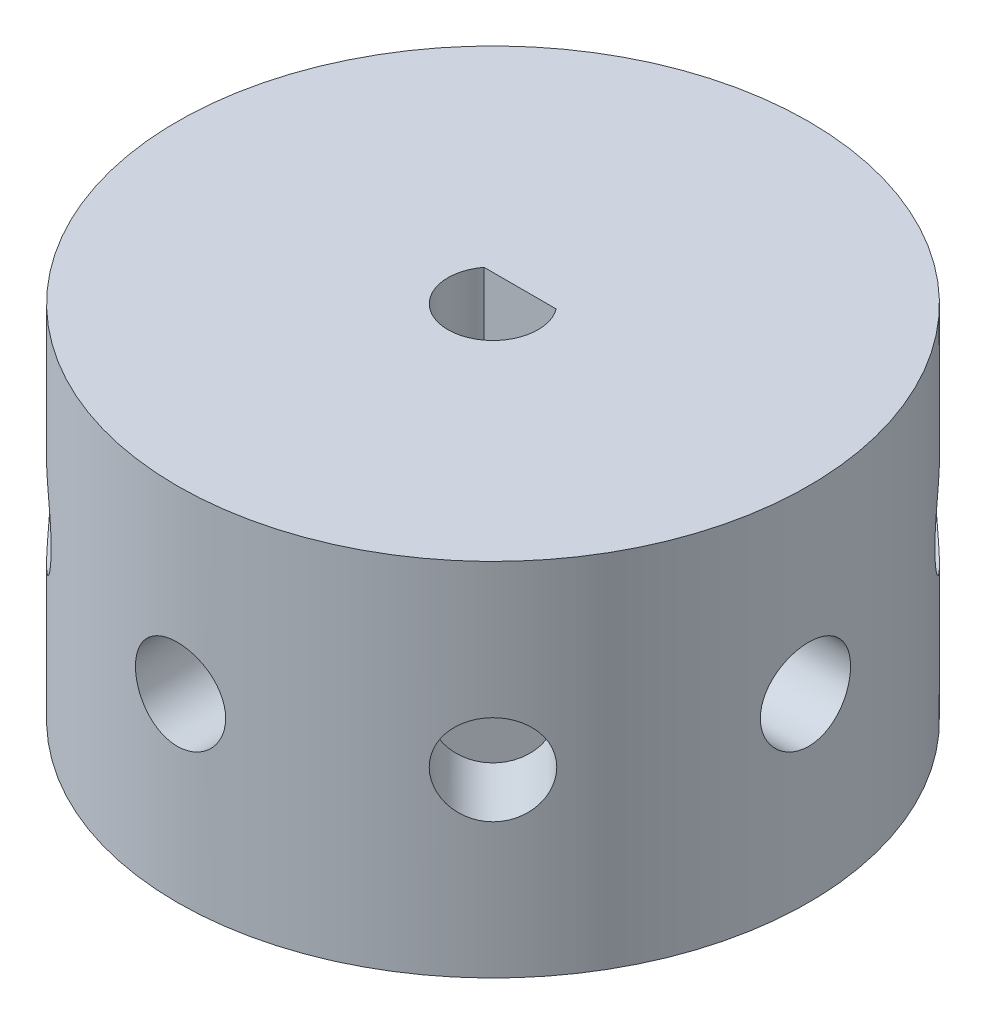
SolidWorks part; units mm, degrees
ref_plane "Front Plane" through (0, 0, 0) normal (0, 0, 1) x (1, 0, 0)
ref_plane "Top Plane" through (0, 0, 0) normal (0, 1, 0) x (1, 0, 0)
ref_plane "Right Plane" through (0, 0, 0) normal (1, 0, 0) x (0, 0, -1)
sketch "Sketch1" plane through (0, 0, 0) normal (0, 1, 0) x (1, 0, 0)
  line L0 (0, 0) -> (0, 3) construction
  line L1 (-4, 3) -> (4, 3)
  circle A0 centre (0, 0) radius 35
  circle A2 centre (0, 0) radius 5
  dimension "D1" = 70
  dimension "D2" = 10
  dimension "D3" = 3
extrude "Boss-Extrude1" add sketch "Sketch1" along normal blind 40 contours A0 A2 | L1 A2
ref_plane "Plane1" through (0, 0, -35) normal (0, 0, -1) x (-1, 0, 0)
sketch "Sketch7" plane through (0, 0, -35) normal (0, 0, -1) x (-1, 0, 0)
  line L0 (0, 0) -> (0, 20) construction
  circle A0 centre (0, 20) radius 5
  dimension "D2" = 10
  dimension "D1" = 20
extrude "Cut-Extrude4" cut sketch "Sketch7" against normal blind 8
pattern_circular "CirPattern1" count 8 over 360 about axis through (0, 0, 0) along (0, 1, 0) of "Cut-Extrude4"
